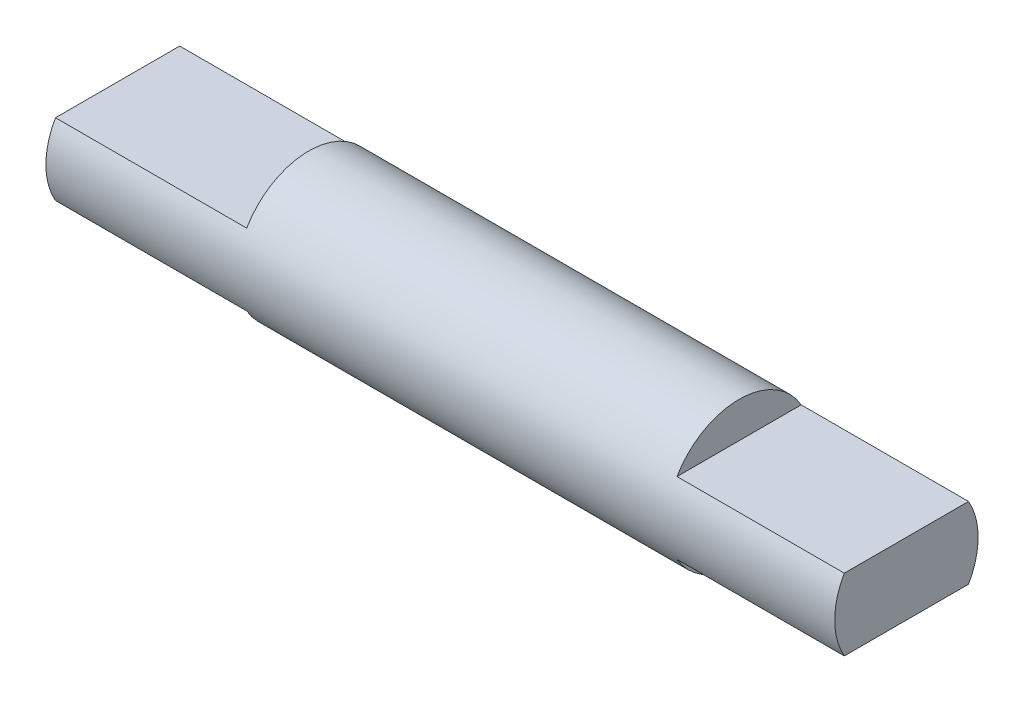
SolidWorks part; units mm, degrees
ref_plane "Front Plane" through (0, 0, 0) normal (0, 0, 1) x (1, 0, 0)
ref_plane "Top Plane" through (0, 0, 0) normal (0, 1, 0) x (1, 0, 0)
ref_plane "Right Plane" through (0, 0, 0) normal (1, 0, 0) x (0, 0, -1)
sketch "Sketch1" plane through (0, 0, 0) normal (1, 0, 0) x (0, 0, -1)
  circle A0 centre (0, 0) radius 3
extrude "Boss-Extrude1" add sketch "Sketch1" along normal blind 33
sketch "Sketch2" plane through (0, 0, 0) normal (-1, 0, 0) x (0, 0, 1)
  line L0 (-2.5981, 1.5) -> (2.5981, 1.5)
  line L2 (-2.5981, -1.5) -> (2.5981, -1.5)
  line L3 (3.3, 0) -> (-3.3, 0) construction
  arc A0 (-2.5981, -1.5) -> (2.5981, -1.5) centre (0, 0) ccw
  arc A1 (2.5981, 1.5) -> (-2.5981, 1.5) centre (0, 0) ccw
  dimension "D2" = 1.5
  dimension "D3" = 3
  dimension "D1" = 3
extrude "Cut-Extrude1" cut sketch "Sketch2" against normal blind 8
sketch "Sketch3" plane through (33, 0, 0) normal (1, 0, 0) x (0, 0, -1)
  line L0 (-2.5981, 1.5) -> (2.5981, 1.5)
  line L2 (-2.5981, -1.5) -> (2.5981, -1.5)
  arc A0 (-2.5981, -1.5) -> (2.5981, -1.5) centre (0, 0) ccw
  arc A1 (2.5981, 1.5) -> (-2.5981, 1.5) centre (0, 0) ccw
  dimension "D1" = 3
extrude "Cut-Extrude2" cut sketch "Sketch3" against normal blind 7
